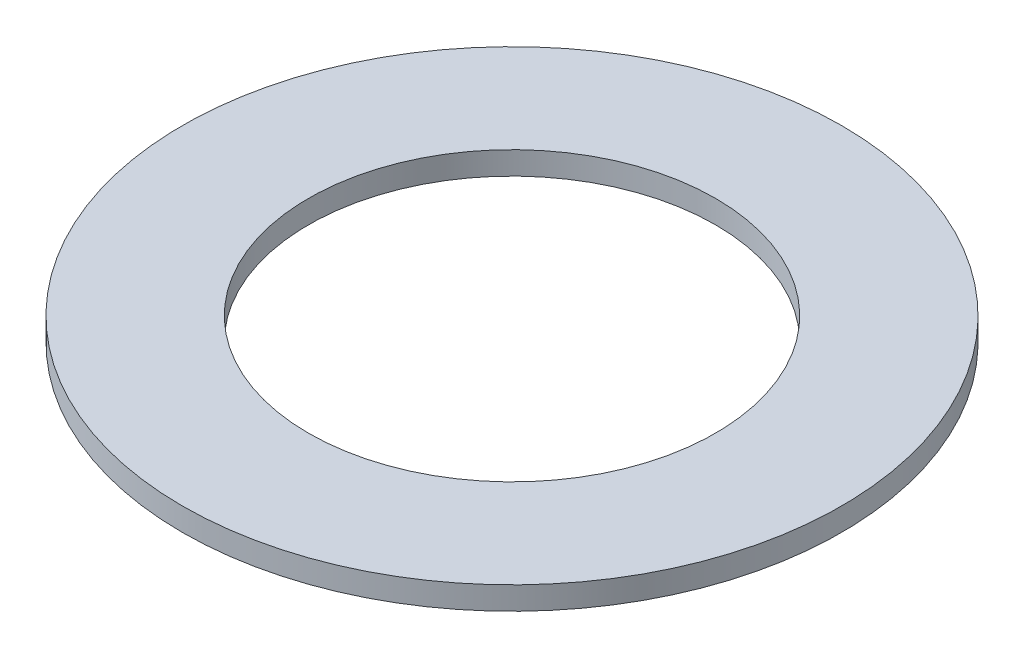
SolidWorks part; units mm, degrees
material "1023 Carbon Steel Sheet (SS)"
ref_plane "Front Plane" through (0, 0, 0) normal (0, 0, 1) x (1, 0, 0)
ref_plane "Top Plane" through (0, 0, 0) normal (0, 1, 0) x (1, 0, 0)
ref_plane "Right Plane" through (0, 0, 0) normal (1, 0, 0) x (0, 0, -1)
sketch "Sketch1" plane through (0, 0, 0) normal (0, 1, 0) x (1, 0, 0)
  circle A0 centre (0, 0) radius 5.75
  circle A1 centre (0, 0) radius 3.55
  dimension "D1" = 11.5
  dimension "D2" = 7.1
extrude "Boss-Extrude1" add sketch "Sketch1" along normal blind 0.4
